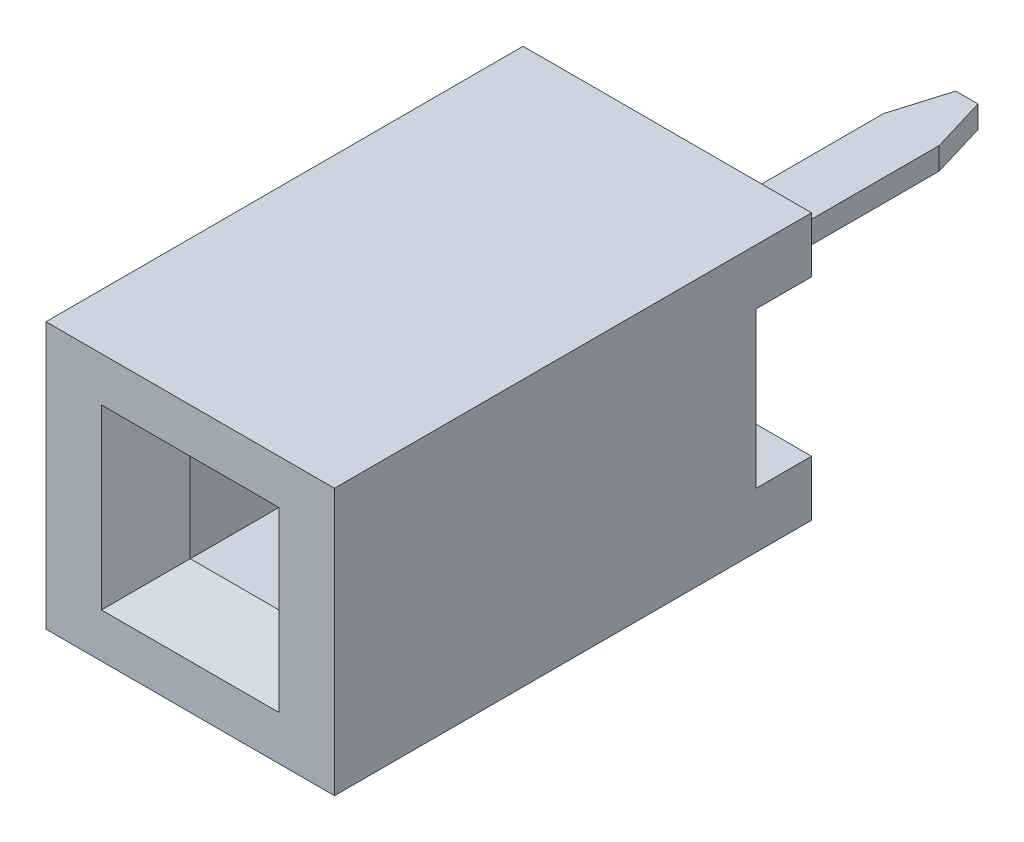
SolidWorks part; units mm, degrees
ref_plane "Front Plane" through (0, 0, 0) normal (0, 0, 1) x (1, 0, 0)
ref_plane "Top Plane" through (0, 0, 0) normal (0, 1, 0) x (1, 0, 0)
ref_plane "Right Plane" through (0, 0, 0) normal (1, 0, 0) x (0, 0, -1)
sketch "Sketch1" plane through (0, 0, 0) normal (1, 0, 0) x (0, -1, 0)
  line L0 (0, 0) -> (0, -4.3) construction
  line L1 (-1.2, 0) -> (1.2, 0)
  line L2 (-1.2, 0) -> (-1.2, -4.3)
  line L3 (-1.2, -4.3) -> (1.2, -4.3)
  line L4 (1.2, 0) -> (1.2, -4.3)
  point P0 (0, 0)
  dimension "D1" = 2.4
  dimension "D2" = 4.3
extrude "Boss-Extrude1" add sketch "Sketch1" along normal mid plane 2.6
sketch "Эскиз1" plane through (1.3, 0, 0) normal (1, 0, 0) x (0, 0, -1)
  line L0 (0, -0.7) -> (-0.5, -0.7)
  line L1 (0, -1.2) -> (0, 1.2) construction
  line L2 (-0.5, -0.7) -> (-0.5, 0.7)
  line L4 (-0.5, 0.7) -> (0, 0.7)
  line L5 (0, 0.7) -> (0, -0.7)
  line L6 (-4.3, -1.2) -> (0, -1.2) construction
  dimension "D1" = 0.5
  dimension "D2" = 0.5
  dimension "D3" = 0.5
extrude "Вырез-Вытянуть1" cut sketch "Эскиз1" against normal through all
sketch "Sketch2" plane through (0, 0, 4.3) normal (0, 0, 1) x (-1, 0, 0)
  line L0 (0, -1.2) -> (0, 1.2) construction
  line L3 (-1.3, -1.2) -> (1.3, -1.2) construction
  line L4 (-0.4, 0.4) -> (0.4, 0.4)
  line L5 (-0.4, 0.4) -> (-0.4, -0.4)
  line L6 (-0.4, -0.4) -> (0.4, -0.4)
  line L7 (0.4, 0.4) -> (0.4, -0.4)
  line L8 (-0.4, 0.4) -> (0.4, -0.4) construction
  line L9 (-0.4, -0.4) -> (0.4, 0.4) construction
  line L10 (-1.3, 1.2) -> (1.3, 1.2) construction
  point P5 (0, 0)
  dimension "D1" = 0.8
extrude "Cut-Extrude1" cut sketch "Sketch2" against normal offset from surface (3.1 mm away) 0.7 up to face at (0, 0, 0.5)
chamfer "Фаска1" distance 0.4 angle 45 4 edges at (0, -0.4, 4.3) (0.4, 0, 4.3) (0, 0.4, 4.3) (-0.4, 0, 4.3)
sketch "Sketch3" plane through (0, 0, 0) normal (0, 1, 0) x (1, 0, 0)
  line L0 (-0.25, 0) -> (-0.25, 2.2)
  line L1 (0.25, 0) -> (0.25, -0.5)
  line L2 (-0.25, 2.2) -> (-0.1, 2.7)
  line L3 (-0.1, 2.7) -> (0.1, 2.7)
  line L4 (0, 2.7) -> (0, 0) construction
  line L5 (-0.25, 0) -> (0.25, 0) construction
  line L6 (0.25, 2.2) -> (0.1, 2.7)
  line L7 (0.25, 0) -> (0.25, 2.2)
  line L8 (0.25, -0.5) -> (-0.25, -0.5)
  line L9 (-0.25, -0.5) -> (-0.25, 0)
  line L10 (-1.3, -0.5) -> (1.3, -0.5) construction
  line L11 (0.25, 2.2) -> (-0.25, 2.2) construction
  line L12 (0.4, -1.2) -> (-0.4, -1.2)
  line L13 (-0.4, -1.2) -> (-0.4, -3.1)
  line L14 (-0.4, -3.1) -> (-0.3, -3.1)
  line L15 (-0.3, -3.1) -> (-0.3, -1.3)
  line L16 (-0.3, -1.3) -> (0.3, -1.3)
  line L17 (0.3, -1.3) -> (0.3, -3.1)
  line L18 (0.3, -3.1) -> (0.4, -3.1)
  line L19 (0.4, -3.1) -> (0.4, -1.2)
  line L20 (-0.4, -1.2) -> (-0.4, -3.9) construction
  line L21 (0.4, -1.2) -> (0.4, -3.9) construction
  line L22 (0.4, -1.2) -> (-0.4, -1.2) construction
  dimension "D1" = 0.5
  dimension "D2" = 0.15
  dimension "D3" = 2.7
  dimension "D4" = 0.5
  dimension "D5" = 1.2
  dimension "D6" = 0.1
  dimension "D7" = 0.1
extrude "Boss-Extrude2" add sketch "Sketch3" along normal mid plane 0.2
pattern_linear "LPattern1" [suppressed] count 3 spacing 2
combine bodies "Соединить1" [suppressed] operation type add bodies to combine 104 103 107 108
